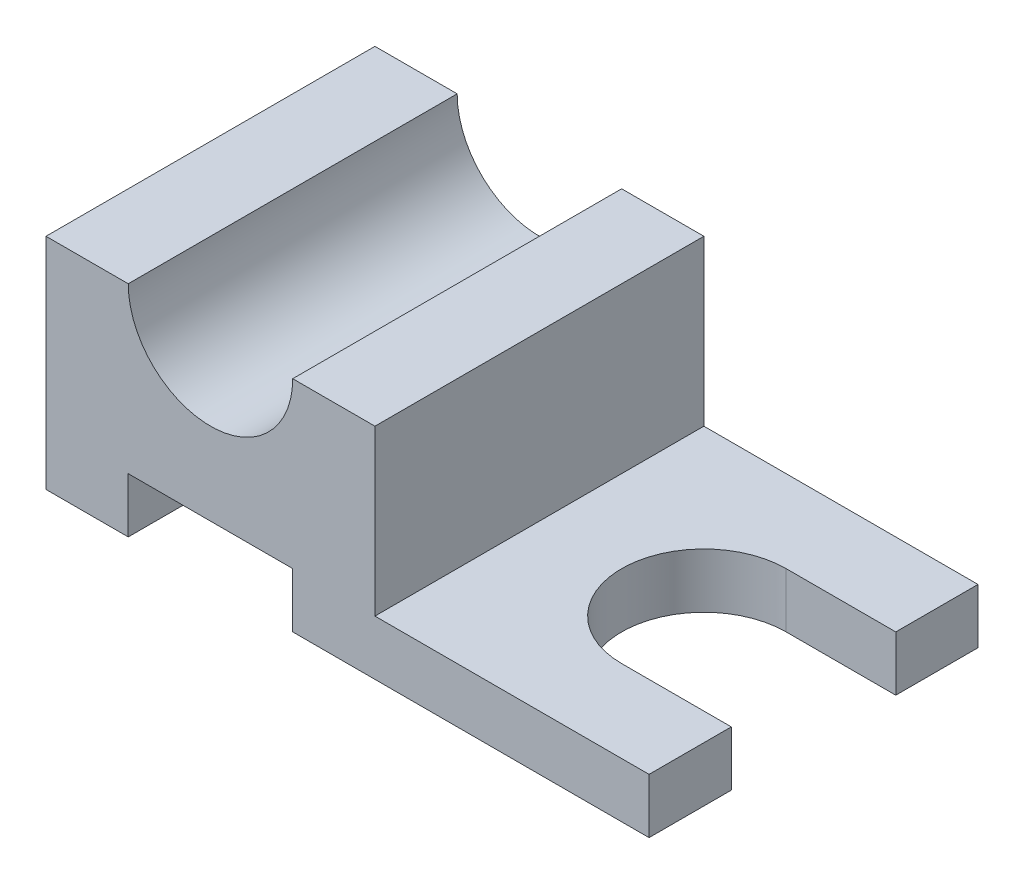
SolidWorks part; units mm, degrees
ref_plane "Front Plane" through (0, 0, 0) normal (0, 0, 1) x (1, 0, 0)
ref_plane "Top Plane" through (0, 0, 0) normal (0, 1, 0) x (1, 0, 0)
ref_plane "Right Plane" through (0, 0, 0) normal (1, 0, 0) x (0, 0, -1)
sketch "Sketch1" plane through (0, 0, 0) normal (0, 0, 1) x (1, 0, 0)
  line L0 (0, 35.3268) -> (0, 20.3268) construction
  line L1 (-30, 50.3268) -> (-30, 10.3268)
  line L2 (30, 50.3268) -> (30, 20.3268)
  line L3 (-15, 50.3268) -> (-30, 50.3268)
  line L4 (15, 50.3268) -> (30, 50.3268)
  line L5 (-30, 50.3268) -> (-15, 50.3268) construction
  line L6 (-30, 10.3268) -> (-15, 10.3268)
  line L7 (-15, 20.3268) -> (15, 20.3268)
  line L8 (-15, 50.3268) -> (-15, 10.3268) construction
  line L9 (15, 50.3268) -> (15, 10.3268) construction
  line L10 (-15, 10.3268) -> (-15, 20.3268)
  line L11 (15, 10.3268) -> (15, 20.3268)
  line L12 (-71.7178, 10.3268) -> (74.9595, 10.3268) construction
  line L13 (-71.7178, 20.3268) -> (74.9595, 20.3268) construction
  line L14 (-71.7178, 50.3268) -> (74.9595, 50.3268) construction
  line L15 (15, 50.3268) -> (30, 50.3268) construction
  line L16 (0, 50.3268) -> (0, -62.3004) construction
  line L17 (15, 10.3268) -> (80, 10.3268)
  line L18 (30, 20.3268) -> (80, 20.3268)
  line L19 (-30, 50.3268) -> (-30, -62.3004) construction
  line L20 (30, 50.3268) -> (30, -62.3004) construction
  line L21 (80, 20.3268) -> (80, 10.3268)
  arc A0 (-15, 50.3268) -> (15, 50.3268) centre (0, 50.3268) ccw
  dimension "D3" = 40
  dimension "D1" = 30
  dimension "D5" = 50
  dimension "D2" = 30
  dimension "D4" = 30
extrude "Boss-Extrude1" add sketch "Sketch1" along normal blind 60
sketch "Sketch2" plane through (0, 20.3268, 0) normal (0, 1, 0) x (1, 0, 0)
  line L0 (80, -15) -> (80, -45)
  line L1 (80, -60) -> (80, 0) construction
  line L2 (80, -15) -> (60, -15)
  line L4 (60, -45) -> (80, -45)
  arc A0 (60, -15) -> (60, -45) centre (60, -30) ccw
  dimension "D1" = 30
extrude "Cut-Extrude1" cut sketch "Sketch2" against normal blind 60 contours L0 L4 A0 L2
